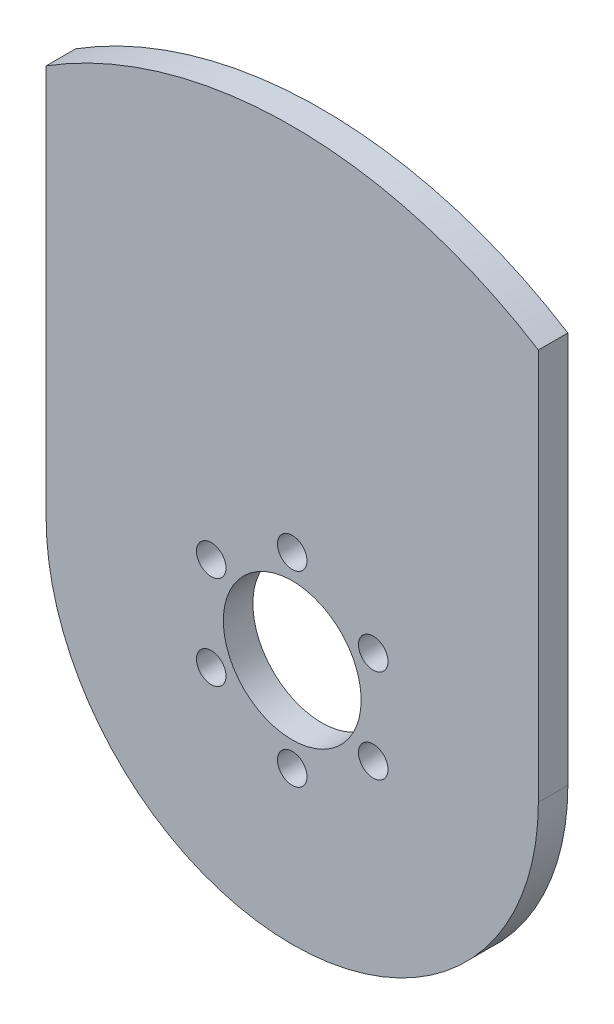
SolidWorks part; units mm, degrees
ref_plane "Plan de face" through (0, 0, 0) normal (0, 0, 1) x (1, 0, 0)
ref_plane "Plan de dessus" through (0, 0, 0) normal (0, 1, 0) x (1, 0, 0)
ref_plane "Plan de droite" through (0, 0, 0) normal (1, 0, 0) x (0, 0, -1)
sketch "Esquisse1" plane through (0, 0, 0) normal (0, 0, 1) x (1, 0, 0)
  circle A0 centre (0, 0) radius 47
  circle A1 centre (0, 0) radius 7
extrude "Boss.-Extru.1" add sketch "Esquisse1" along normal blind 3
sketch "Esquisse2" plane through (0, 0, 3) normal (0, 0, 1) x (1, 0, 0)
  line L0 (-25, 0) -> (25, 0)
  line L1 (-25, 0) -> (-25, 50.4793)
  line L2 (25, 0) -> (25, 50.4793)
  line L3 (-25, 50.4793) -> (25, 50.4793)
  circle A0 centre (0, 9.5) radius 1.5
  circle A1 centre (8.2272, 4.75) radius 1.5
  circle A2 centre (8.2272, -4.75) radius 1.5
  circle A3 centre (0, -9.5) radius 1.5
  circle A4 centre (-8.2272, -4.75) radius 1.5
  circle A5 centre (-8.2272, 4.75) radius 1.5
  circle A6 centre (0, 0) radius 25
  point P4 (0, 0)
  point P12 (0, 0)
  point P33 (0, 0)
  circle M3 centre (0, 0) radius 47
  dimension "D1" = 9.5
  dimension "D2" = 6
extrude "Enlèv. mat.-Extru.1" cut sketch "Esquisse2" against normal through all contours A6 L1 L2 M3 | A3 | A4 | A5 | A2 | A0 | A1
